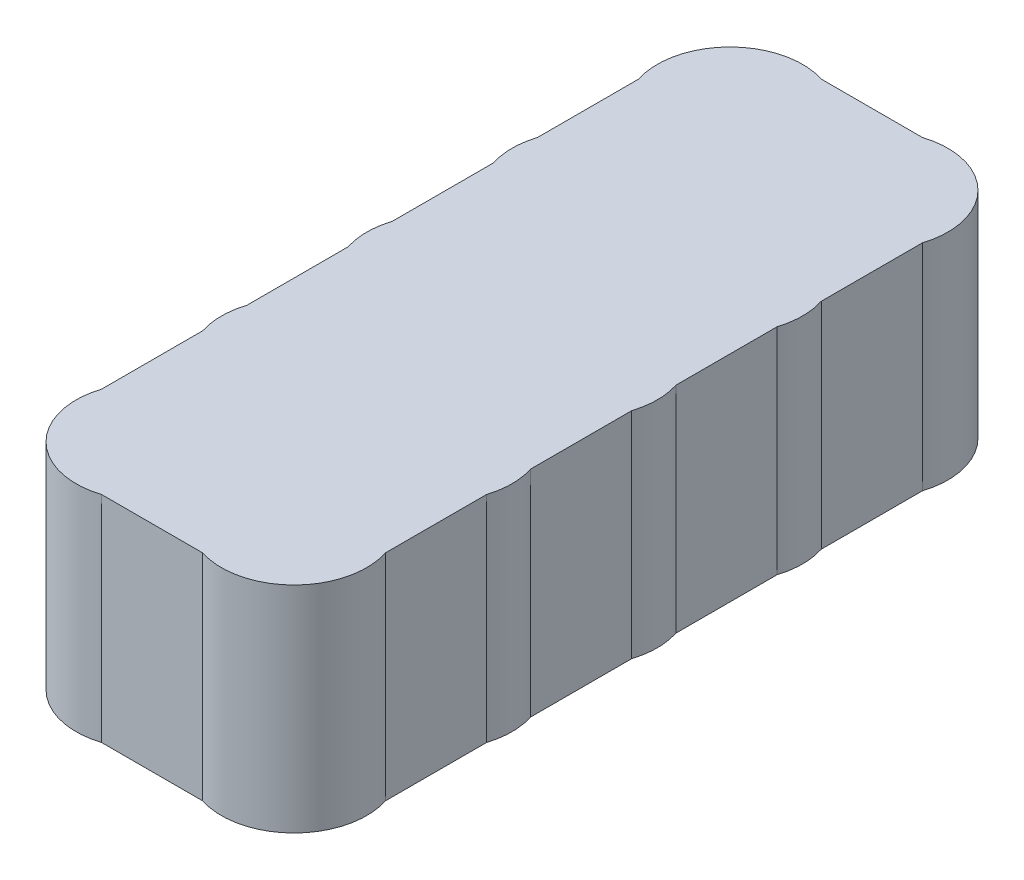
SolidWorks part; units mm, degrees
material "PC High Viscosity"
ref_plane "Front Plane" through (0, 0, 0) normal (0, 0, 1) x (1, 0, 0)
ref_plane "Top Plane" through (0, 0, 0) normal (0, 1, 0) x (1, 0, 0)
ref_plane "Right Plane" through (0, 0, 0) normal (1, 0, 0) x (0, 0, -1)
sketch "Sketch1" plane through (0, 0, 0) normal (0, 1, 0) x (1, 0, 0)
  arc A0 (0, 11.5) -> (11.5, 0) centre (0, 0) ccw
  arc A1 (11.5, 0) -> (23, 11.5) centre (23, 0) ccw
  arc A2 (23, 11.5) -> (23, 34.5) centre (23, 23) ccw
  arc A3 (23, 34.5) -> (23, 57.5) centre (23, 46) ccw
  arc A4 (23, 57.5) -> (23, 80.5) centre (23, 69) ccw
  arc A5 (23, 80.5) -> (11.5, 92) centre (23, 92) ccw
  arc A6 (0, 34.5) -> (0, 11.5) centre (0, 23) ccw
  arc A7 (0, 57.5) -> (0, 34.5) centre (0, 46) ccw
  arc A8 (0, 80.5) -> (0, 57.5) centre (0, 69) ccw
  arc A9 (11.5, 92) -> (0, 80.5) centre (0, 92) ccw
  dimension "D1" = 23
  dimension "D7" = 11.5
  dimension "D4" = 26.565
  dimension "D5" = 23
  dimension "D2" = 2
  dimension "D3" = 5
extrude "Boss-Extrude1" add sketch "Sketch1" along normal blind 34
sketch "Sketch2" plane through (0, 34, 0) normal (0, 1, 0) x (1, 0, 0)
  line L0 (-10.9545, 88.5) -> (-10.9545, 72.5)
  line L1 (-10.9545, 72.5) -> (-10.9545, 3.5)
  line L3 (33.9545, 88.5) -> (33.9545, -3.5)
  line L4 (3.5, 102.9545) -> (19.5, 102.9545)
  line L5 (-10.9545, 88.5) -> (3.5, 102.9545)
  line L6 (19.5, 102.9545) -> (33.9545, 88.5)
  line L7 (3.5, -10.9545) -> (19.5, -10.9545)
  line L8 (3.5, -10.9545) -> (-10.9545, 3.5)
  line L9 (19.5, -10.9545) -> (33.9545, -3.5)
  arc A0 (11.5, 92) -> (0, 80.5) centre (0, 92) ccw construction
  arc A1 (0, 80.5) -> (0, 57.5) centre (0, 69) ccw construction
  arc A2 (0, 11.5) -> (11.5, 0) centre (0, 0) ccw construction
  arc A3 (23, 80.5) -> (11.5, 92) centre (23, 92) ccw construction
  arc A4 (11.5, 0) -> (23, 11.5) centre (23, 0) ccw construction
  point P8 (-10.9545, 80.5)
  dimension "D1" = 16
extrude "Boss-Extrude2" add sketch "Sketch2" against normal up to surface (34 mm away) up to face at (11.5, 0, -46)
